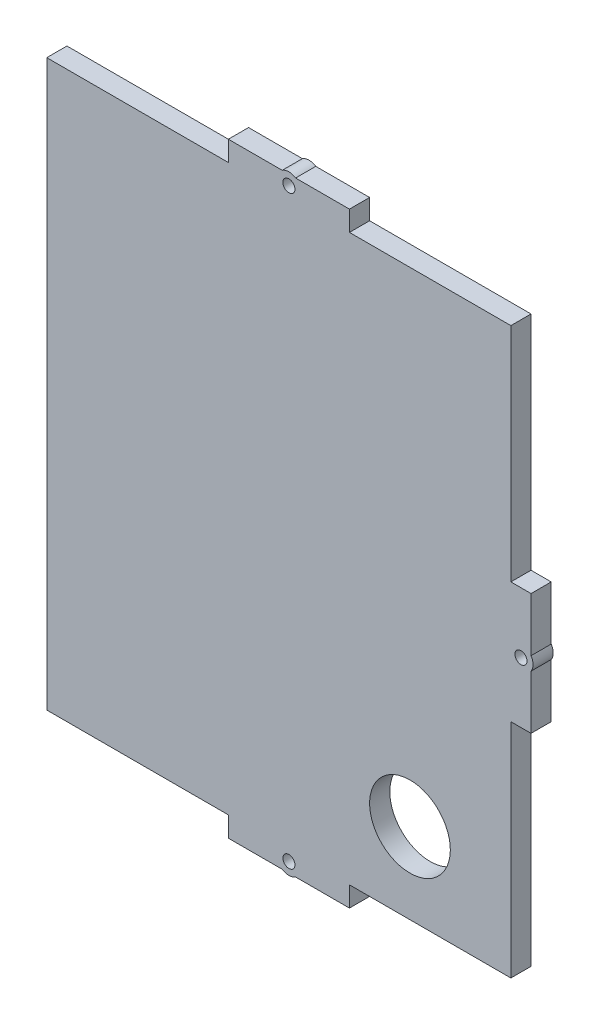
SolidWorks part; units mm, degrees
ref_plane "Plan de face" through (0, 0, 0) normal (0, 0, 1) x (1, 0, 0)
ref_plane "Plan de dessus" through (0, 0, 0) normal (0, 1, 0) x (1, 0, 0)
ref_plane "Plan de droite" through (0, 0, 0) normal (1, 0, 0) x (0, 0, -1)
sketch "Esquisse1" plane through (0, 0, 0) normal (0, 0, 1) x (1, 0, 0)
  line L0 (0, 124.0637) -> (0, -110.1992) construction
  line L1 (-55, 70) -> (55, 70)
  line L2 (-55, 70) -> (-55, -70)
  line L3 (-55, -70) -> (55, -70)
  line L4 (55, 70) -> (55, -70)
  line L5 (-55, 70) -> (55, -70) construction
  line L6 (-55, -70) -> (55, 70) construction
  line L7 (-140.9438, 0) -> (184.1558, 0) construction
  line L8 (1.6583, 75) -> (15, 75)
  line L9 (-15, 75) -> (-1.6583, 75)
  line L10 (-15, 75) -> (-15, 70)
  line L11 (-15, 70) -> (15, 70)
  line L12 (15, 75) -> (15, 70)
  line L13 (-15, 75) -> (15, 70) construction
  line L14 (-15, 70) -> (15, 75) construction
  line L15 (-15, -75) -> (-1.6583, -75)
  line L16 (-15, -75) -> (-15, -70)
  line L17 (-15, -70) -> (15, -70)
  line L18 (15, -75) -> (15, -70)
  line L19 (1.6583, -75) -> (15, -75)
  line L24 (-55, 15) -> (-55, -15)
  line L27 (60, 15) -> (55, 15)
  line L28 (55, 15) -> (55, -15)
  line L29 (60, -15) -> (55, -15)
  line L30 (60, -1.6583) -> (60, -15)
  line L31 (60, 15) -> (60, 1.6583)
  circle A0 centre (0, 72.5) radius 1.5
  arc A1 (1.6583, 75) -> (-1.6583, 75) centre (0, 72.5) ccw
  circle A2 centre (0, -72.5) radius 1.5
  arc A3 (1.6583, -75) -> (-1.6583, -75) centre (0, -72.5) cw
  circle A6 centre (57.5, 0) radius 1.5
  arc A7 (60, 1.6583) -> (60, -1.6583) centre (57.5, 0) cw
  point P0 (0, 0)
  point P10 (0, 72.5)
  point P27 (-62.5, 0)
  dimension "D5" = 3
  dimension "D6" = 6
  dimension "D1" = 140
  dimension "D2" = 110
  dimension "D3" = 5
  dimension "D4" = 30
extrude "Boss.-Extru.1" add sketch "Esquisse1" along normal blind 5
sketch "Esquisse2" plane through (-55, 0, 0) normal (-1, 0, 0) x (0, 0, 1)
  line L4 (0, 70) -> (0, -70)
  line L5 (0, -70) -> (5, -70)
  line L6 (5, -70) -> (5, 70)
  line L7 (5, 70) -> (0, 70)
  line L8 (0, 70) -> (0, -70)
  line L9 (0, -70) -> (5, -70)
  line L10 (5, -70) -> (5, 70)
  line L11 (5, 70) -> (0, 70)
  dimension "D1" = 0
extrude "Boss.-Extru.2" add sketch "Esquisse2" along normal blind 5
sketch "Esquisse3" plane through (0, 0, 5) normal (0, 0, 1) x (1, 0, 0)
  line L0 (15, -70) -> (55, -70) construction
  line L1 (55, -15) -> (55, -70) construction
  circle A0 centre (30, -50) radius 10
  dimension "D1" = 20
  dimension "D2" = 20
  dimension "D3" = 25
extrude "Enlèv. mat.-Extru.1" cut sketch "Esquisse3" against normal blind 10
